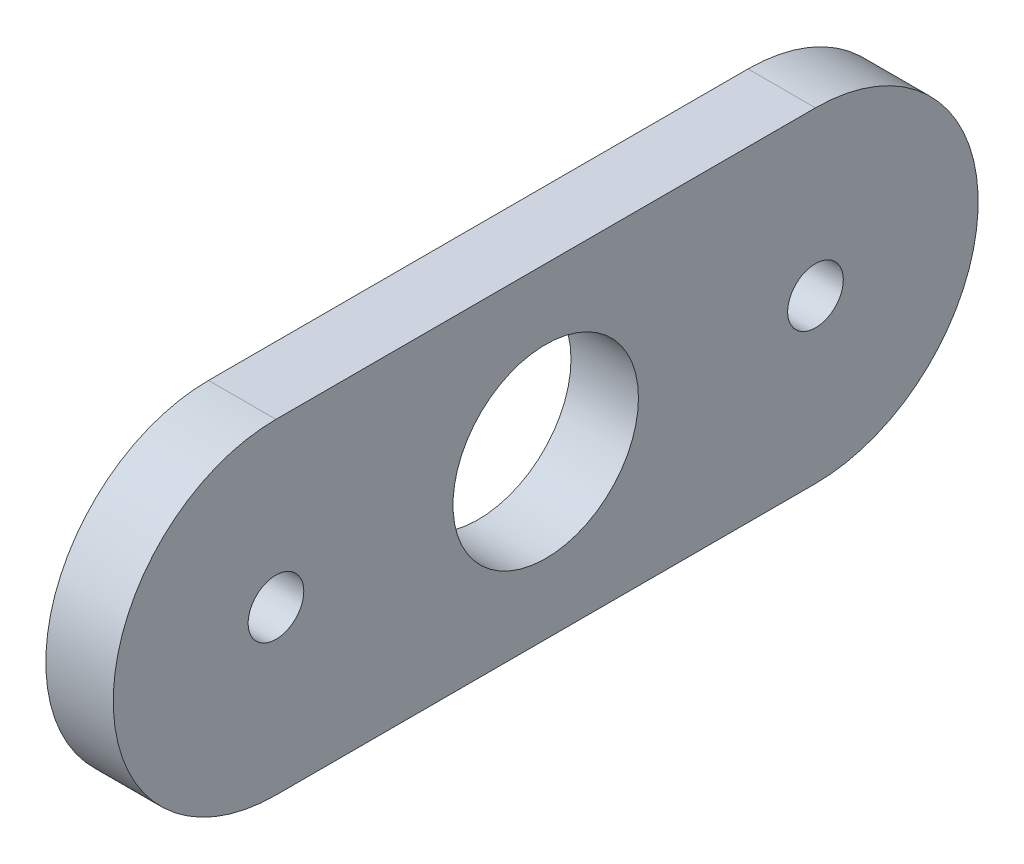
SolidWorks part; units mm, degrees
ref_plane "Front Plane" through (0, 0, 0) normal (0, 0, 1) x (1, 0, 0)
ref_plane "Top Plane" through (0, 0, 0) normal (0, 1, 0) x (1, 0, 0)
ref_plane "Right Plane" through (0, 0, 0) normal (1, 0, 0) x (0, 0, -1)
sketch "Sketch1" plane through (0, 0, 0) normal (1, 0, 0) x (0, 0, -1)
  line L0 (-16, 0) -> (16, 0) construction
  line L1 (-16, 9.65) -> (16, 9.65)
  line L2 (-16, -9.65) -> (16, -9.65)
  arc A0 (-16, 9.65) -> (-16, -9.65) centre (-16, 0) ccw
  arc A1 (16, -9.65) -> (16, 9.65) centre (16, 0) ccw
  circle A2 centre (-16, 0) radius 1.65
  circle A3 centre (16, 0) radius 1.65
  circle A4 centre (0, 0) radius 5.5
  point P2 (0, 0)
  dimension "D1" = 3.3
  dimension "D2" = 8
  dimension "D4" = 11
  dimension "D3" = 32
extrude "Boss-Extrude1" add sketch "Sketch1" along normal blind 4
